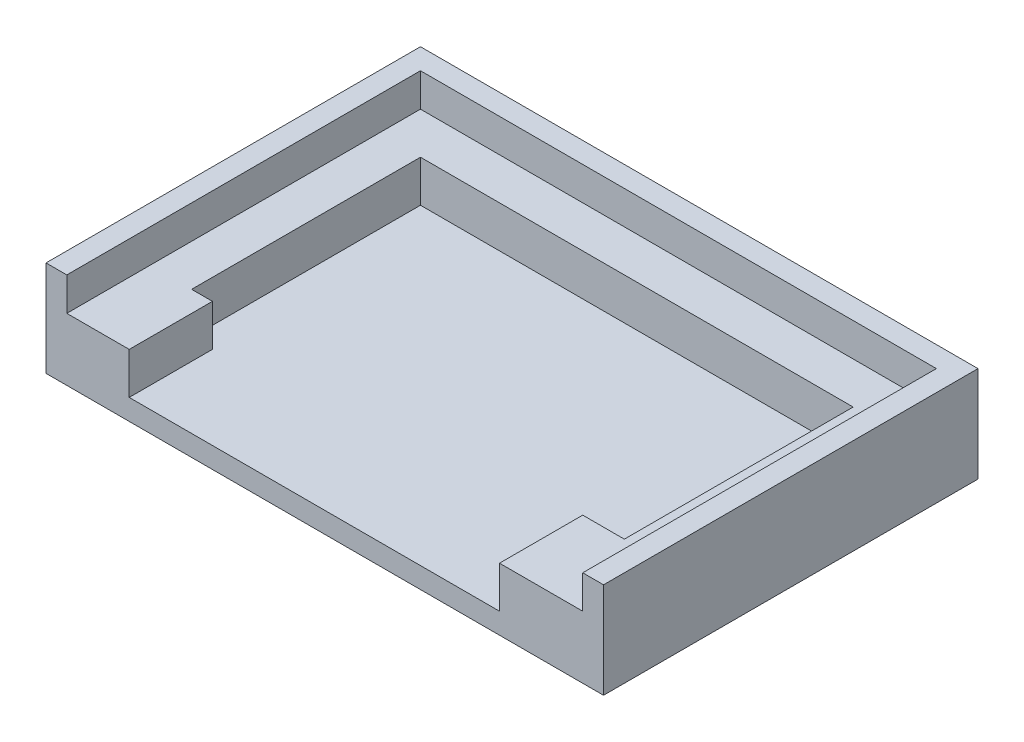
SolidWorks part; units mm, degrees
ref_plane "Спереди" through (0, 0, 0) normal (0, 0, 1) x (1, 0, 0)
ref_plane "Сверху" through (0, 0, 0) normal (0, 1, 0) x (1, 0, 0)
ref_plane "Справа" through (0, 0, 0) normal (1, 0, 0) x (0, 0, -1)
sketch "Эскиз1" plane through (0, 0, 0) normal (0, 1, 0) x (1, 0, 0)
  line L1 (-67, -45) -> (67, -45)
  line L2 (-67, -45) -> (-67, 45)
  line L3 (-67, 45) -> (67, 45)
  line L4 (67, -45) -> (67, 45)
  line L5 (-67, -45) -> (67, 45) construction
  line L6 (-67, 45) -> (67, -45) construction
  point P0 (0, 0)
  dimension "D1" = 90
  dimension "D2" = 134
extrude "Бобышка-Вытянуть1" add sketch "Эскиз1" along normal blind 5
sketch "Эскиз2" plane through (0, 5, 0) normal (0, 1, 0) x (1, 0, 0)
  line L0 (-67, -45) -> (67, -45) construction
  line L1 (-47, -45) -> (-67, -45)
  line L2 (-47, -45) -> (-47, -25)
  line L3 (-47, -25) -> (-52, -25)
  line L4 (-67, -45) -> (-67, -25)
  line L5 (-67, 45) -> (-67, -45) construction
  line L6 (67, 45) -> (-67, 45) construction
  line L7 (-67, -45) -> (-51.5, -45)
  line L8 (-67, -45) -> (-67, 45)
  line L9 (-67, 45) -> (-51.5, 45)
  line L10 (-52, -25) -> (-52, 30)
  line L11 (67, -45) -> (67, 45) construction
  line L12 (-67, 45) -> (67, 45)
  line L13 (-67, 45) -> (-67, 30)
  line L14 (-52, 30) -> (52, 30)
  line L15 (67, 45) -> (67, 30)
  line L17 (67, -45) -> (51.5, -45)
  line L18 (67, -45) -> (67, 45)
  line L19 (67, 45) -> (51.5, 45)
  line L20 (52, -25) -> (52, 30)
  line L21 (67, -45) -> (42, -45)
  line L22 (67, -45) -> (67, -25)
  line L23 (52, -25) -> (42, -25)
  line L24 (42, -45) -> (42, -25)
  line M17 (67, -45) -> (67, 45)
  line M18 (67, 45) -> (-67, 45)
  line M19 (-67, 45) -> (-67, -45)
  line M20 (-67, -45) -> (67, -45)
  dimension "D1" = 20
  dimension "D2" = 15
  dimension "D3" = 15
  dimension "D4" = 15
  dimension "D5" = 20
  dimension "D6" = 10
  dimension "D7" = 5
extrude "Бобышка-Вытянуть2" add sketch "Эскиз2" along normal blind 10 contours L24 L18 L12 L8 L1 L2 L3 L10 L14 L20 L23 M20 M17 M18 M19
sketch "Эскиз3" plane through (0, 15, 0) normal (0, 1, 0) x (1, 0, 0)
  line L0 (67, 45) -> (-67, 45) construction
  line L1 (67, -45) -> (62, -45)
  line L2 (67, -45) -> (67, 45)
  line L3 (67, 45) -> (61.5, 45)
  line L4 (62, -45) -> (62, 40)
  line L6 (-67, -45) -> (-62, -45)
  line L7 (-67, -45) -> (-67, 45)
  line L8 (-67, 45) -> (-61.5, 45)
  line L9 (-62, -45) -> (-62, 40)
  line L10 (62, 40) -> (-62, 40)
  line L11 (67, 40) -> (67, 45)
  line L12 (67, 45) -> (-67, 45)
  line L13 (-67, 40) -> (-67, 45)
  line M12 (42, -45) -> (67, -45)
  line M13 (67, -45) -> (67, 45)
  line M14 (67, 45) -> (-67, 45)
  line M15 (-67, 45) -> (-67, -45)
  line M16 (-67, -45) -> (-47, -45)
  dimension "D1" = 5
  dimension "D2" = 5
  dimension "D3" = 5
extrude "Бобышка-Вытянуть3" add sketch "Эскиз3" along normal blind 8 contours L10 L4 L2 L7 L9 M12 M13 M14 M15 M16
